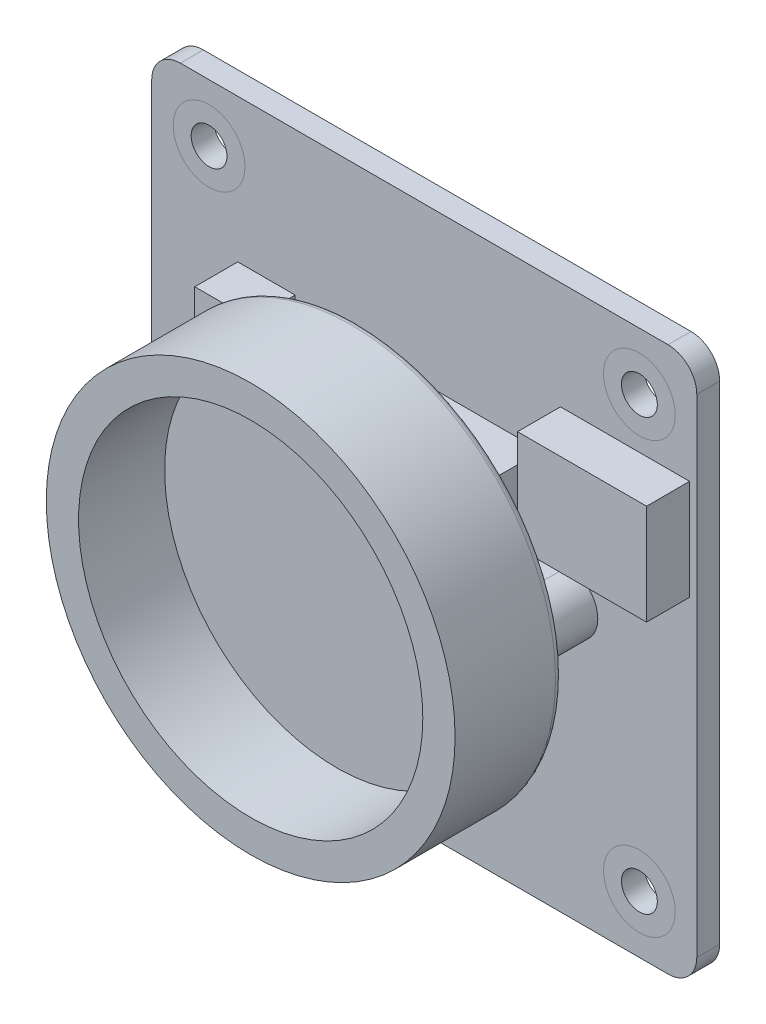
SolidWorks part; units mm, degrees
ref_plane "Front Plane" through (0, 0, 0) normal (0, 0, 1) x (1, 0, 0)
ref_plane "Top Plane" through (0, 0, 0) normal (0, 1, 0) x (1, 0, 0)
ref_plane "Right Plane" through (0, 0, 0) normal (1, 0, 0) x (0, 0, -1)
sketch "Sketch1" plane through (0, 0, 0) normal (0, 0, 1) x (1, 0, 0)
  line L1 (-19, 19) -> (19, 19)
  line L2 (-19, 19) -> (-19, -19)
  line L3 (-19, -19) -> (19, -19)
  line L4 (19, 19) -> (19, -19)
  line L5 (-19, 19) -> (19, -19) construction
  line L6 (-19, -19) -> (19, 19) construction
  point P0 (0, 0)
  dimension "D1" = 38
  dimension "D2" = 38
extrude "Boss-Extrude1" add sketch "Sketch1" along normal blind 1.6
sketch "Sketch2" plane through (0, 0, 1.6) normal (0, 0, 1) x (1, 0, 0)
  line L0 (0, 0) -> (-35355.3391, 35355.3391) construction
  line L1 (0, -1000) -> (0, 49000) construction
  line L2 (-1000, 0) -> (49000, 0) construction
  circle A0 centre (-15, 15) radius 1.25
  circle A1 centre (15, 15) radius 1.25
  circle A2 centre (15, -15) radius 1.25
  circle A3 centre (-15, -15) radius 1.25
  dimension "D1" = 2.5
  dimension "D2" = 30
extrude "Cut-Extrude1" cut sketch "Sketch2" against normal through all
fillet "Fillet1" radius 2 4 edges at (-19, -19, 0.8) (19, -19, 0.8) (19, 19, 0.8) (-19, 19, 0.8)
sketch "Sketch3" plane through (0, 0, 1.6) normal (0, 0, 1) x (1, 0, 0)
  line L0 (-1000, 0) -> (49000, 0) construction
  line L1 (0, -1000) -> (0, 49000) construction
  line L2 (-8.15, 8.15) -> (8.15, 8.15)
  line L3 (-8.15, 8.15) -> (-8.15, -8.15)
  line L4 (-8.15, -8.15) -> (8.15, -8.15)
  line L5 (8.15, 8.15) -> (8.15, -8.15)
  line L6 (-8.15, 8.15) -> (8.15, -8.15) construction
  line L7 (-8.15, -8.15) -> (8.15, 8.15) construction
  line L9 (-10, -2.1) -> (10, -2.1)
  line L10 (-10, -2.1) -> (-10, 2.1)
  line L11 (-10, 2.1) -> (10, 2.1)
  line L12 (10, -2.1) -> (10, 2.1)
  line L13 (-10, -2.1) -> (10, 2.1) construction
  line L14 (-10, 2.1) -> (10, -2.1) construction
  circle A0 centre (10, 0) radius 2.1
  circle A1 centre (-10, 0) radius 2.1
  point P1 (0, 0)
  point P14 (0, 0)
  dimension "D3" = 4.2
  dimension "D1" = 16.3
  dimension "D2" = 20
extrude "Boss-Extrude2" add sketch "Sketch3" along normal blind 4.6 separate body contours L3 L4 L5 L2 | L11 L12 L9 L10 | A1 | A0
sketch "Sketch4" plane through (0, 0, 6.2) normal (0, 0, 1) x (1, 0, 0)
  circle A0 centre (0, 0) radius 14.25
  dimension "D1" = 28.5
extrude "Boss-Extrude3" add sketch "Sketch4" along normal blind 7.5
sketch "Sketch5" plane through (0, 0, 13.7) normal (0, 0, 1) x (1, 0, 0)
  circle A1 centre (0, 0) radius 12
  dimension "D1" = 24
extrude "Cut-Extrude2" cut sketch "Sketch5" against normal blind 6
fillet "Fillet2" radius 0.5 5 edges at (-8.15, 2.1, 3.9) (-8.15, -2.1, 3.9) (8.15, -2.1, 3.9) (8.15, 2.1, 3.9) (14.25, 0, 6.2)
sketch "Sketch6" plane through (0, 0, 0) normal (0, 0, -1) x (-1, 0, 0)
  line L0 (0, -1000) -> (0, 49000) construction
  circle A0 centre (-10, 0) radius 1.75
  circle A1 centre (10, 0) radius 1.75
  dimension "D1" = 3.5
extrude "Boss-Extrude4" add sketch "Sketch6" along normal blind 1 separate body
fillet "Fillet3" radius 0.8 1 edges at (8.25, 0, -1)
fillet "Fillet4" radius 0.8 1 edges at (-8.25, 0, -1)
sketch "Sketch7" plane through (0, 0, 0) normal (0, 0, -1) x (-1, 0, 0)
  circle A0 centre (-15, 15) radius 2.5
  circle A1 centre (15, 15) radius 2.5
  circle A2 centre (15, -15) radius 2.5
  circle A3 centre (-15, -15) radius 2.5
  dimension "D1" = 5
split line "Split Line1"
sketch "Sketch8" plane through (0, 0, 1.6) normal (0, 0, 1) x (1, 0, 0)
  line L0 (19, -17) -> (19, 17) construction
  line L1 (9.5, 11.5) -> (18.5, 11.5)
  line L2 (9.5, 11.5) -> (9.5, 4.5)
  line L3 (9.5, 4.5) -> (18.5, 4.5)
  line L4 (18.5, 11.5) -> (18.5, 4.5)
  line L5 (9.5, 11.5) -> (18.5, 4.5) construction
  line L6 (9.5, 4.5) -> (18.5, 11.5) construction
  line L7 (17, 19) -> (-17, 19) construction
  line L8 (-13, 9) -> (-9, 9)
  line L9 (-13, 9) -> (-13, 3)
  line L10 (-13, 3) -> (-9, 3)
  line L11 (-9, 9) -> (-9, 3)
  line L12 (-13, 9) -> (-9, 3) construction
  line L13 (-13, 3) -> (-9, 9) construction
  line L18 (-13, -3) -> (-9, -3)
  line L19 (-9, -9) -> (-9, -3)
  line L20 (-19, 17) -> (-19, -17) construction
  line L21 (-1000, 0) -> (49000, 0) construction
  line L22 (-13, -9) -> (-9, -9)
  line L23 (-13, -9) -> (-13, -3)
  circle A1 centre (15, 15) radius 2.5 construction
  point P0 (14, 8)
  point P5 (15, 12.5)
  point P10 (-11, 6)
  point P25 (0, 0)
  dimension "D1" = 1
  dimension "D2" = 0.5
  dimension "D3" = 7
  dimension "D4" = 9
  dimension "D5" = 10
  dimension "D6" = 6
  dimension "D7" = 4
  dimension "D8" = 6
extrude "Boss-Extrude5" add sketch "Sketch8" along normal blind 3 separate body
